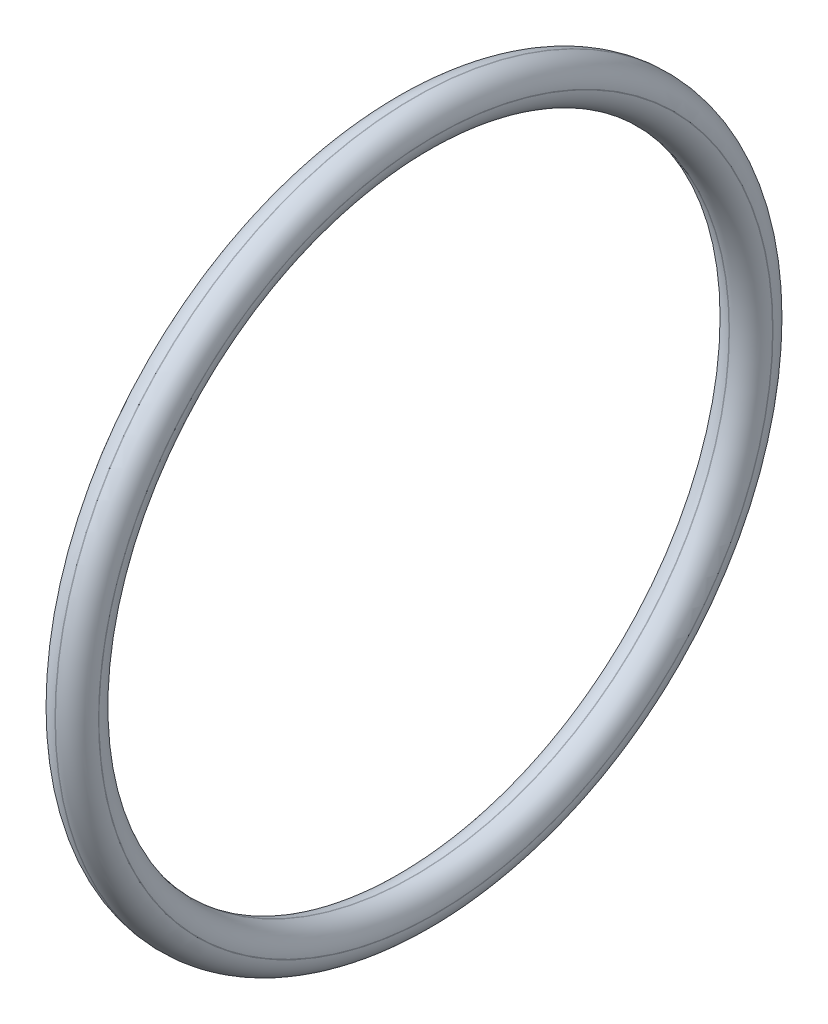
SolidWorks part; units mm, degrees
ref_plane "Plano frontal" through (0, 0, 0) normal (0, 0, 1) x (1, 0, 0)
ref_plane "Plano superior" through (0, 0, 0) normal (0, 1, 0) x (1, 0, 0)
ref_plane "Plano direito" through (0, 0, 0) normal (1, 0, 0) x (0, 0, -1)
sketch "Esboço2" plane through (0, 0, 0) normal (1, 0, 0) x (0, 0, -1)
  circle A0 centre (0, 0) radius 7
  circle A1 centre (0, 0) radius 6.15
  dimension "D1" = 14
  dimension "D2" = 0.85
extrude "Ressalto-extrusão1" add sketch "Esboço2" along normal blind 0.85
fillet "Filete5" radius 0.42 4 edges at (0, 0, -7) (0.85, 0, -7) (0, 0, -6.15) (0.85, 0, -6.15)
